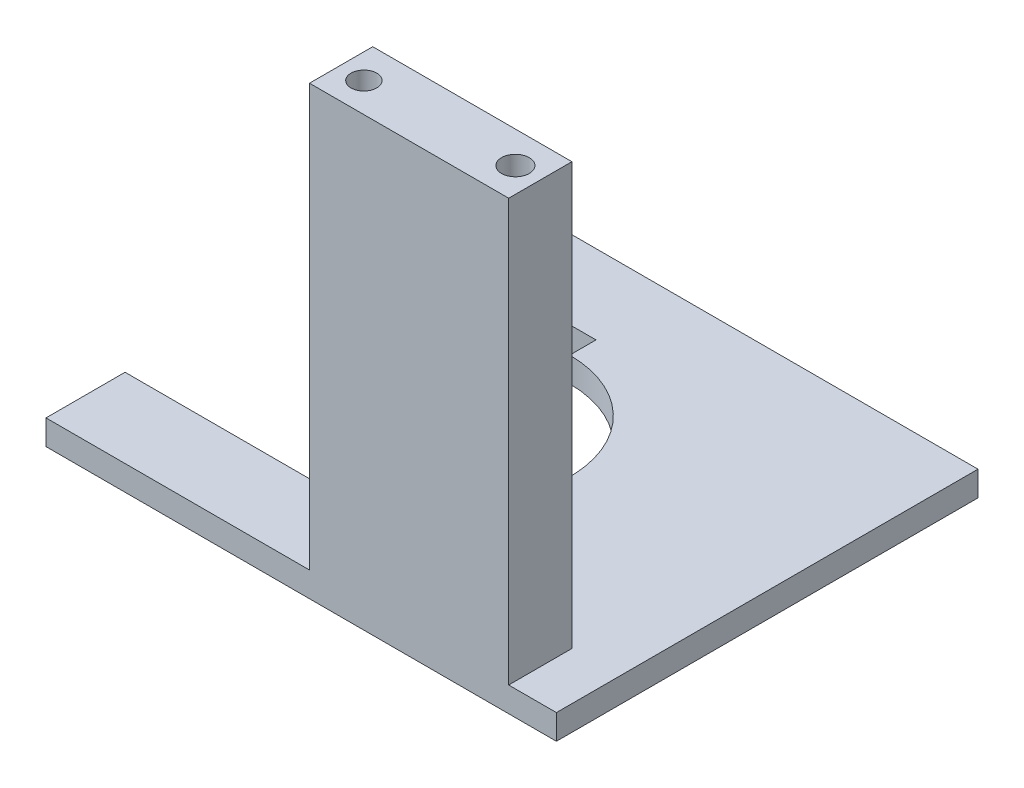
SolidWorks part; units mm, degrees
ref_plane "Front Plane" through (0, 0, 0) normal (0, 0, 1) x (1, 0, 0)
ref_plane "Top Plane" through (0, 0, 0) normal (0, 1, 0) x (1, 0, 0)
ref_plane "Right Plane" through (0, 0, 0) normal (1, 0, 0) x (0, 0, -1)
sketch "Sketch1" plane through (0, 0, 0) normal (0, 1, 0) x (1, 0, 0)
  line L1 (0, 0) -> (61.5, 0)
  line L2 (0, 0) -> (0, -9.525)
  line L3 (0, -50.8) -> (61.5, -50.8)
  line L4 (61.5, 0) -> (61.5, -50.8)
  line L6 (0, -41.275) -> (0, -50.8)
  line L8 (0, -41.275) -> (25, -41.275)
  line L10 (0, -9.525) -> (25, -9.525)
  line L11 (25, -41.275) -> (25, -38.1)
  line L12 (25, -12.7) -> (25, -9.525)
  arc A0 (25, -38.1) -> (25, -12.7) centre (25, -25.4) ccw
  dimension "D1" = 25
  dimension "D4" = 25.4
  dimension "D5" = 25.4
  dimension "D2" = 50.8
  dimension "D3" = 61.5
  dimension "D6" = 31.75
  dimension "D7" = 9.525
extrude "Boss-Extrude1" add sketch "Sketch1" along normal blind 3
sketch "Sketch2" plane through (0, 3, 0) normal (0, 1, 0) x (1, 0, 0)
  line L0 (0, -50.8) -> (61.5, -50.8) construction
  line L1 (31.75, -50.8) -> (55.75, -50.8)
  line L2 (31.75, -50.8) -> (31.75, -43.18)
  line L3 (31.75, -43.18) -> (55.75, -43.18)
  line L4 (55.75, -50.8) -> (55.75, -43.18)
  line L5 (0, -41.275) -> (0, -50.8) construction
  circle A0 centre (34.75, -47.2451) radius 1.5516
  circle A1 centre (52.7482, -46.99) radius 1.6645
  dimension "D2" = 18
  dimension "D3" = 3
  dimension "D5" = 3.81
  dimension "D1" = 24
  dimension "D4" = 7.62
  dimension "D6" = 31.75
extrude "Boss-Extrude2" add sketch "Sketch2" along normal blind 50.8
